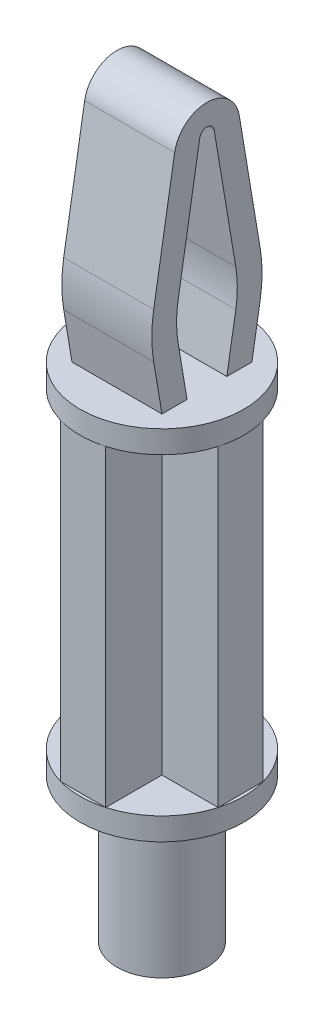
SolidWorks part; units mm, degrees
ref_plane "Front Plane" through (0, 0, 0) normal (0, 0, 1) x (1, 0, 0)
ref_plane "Top Plane" through (0, 0, 0) normal (0, 1, 0) x (1, 0, 0)
ref_plane "Right Plane" through (0, 0, 0) normal (1, 0, 0) x (0, 0, -1)
sketch "Sketch1" plane through (0, 0, 0) normal (0, 1, 0) x (1, 0, 0)
  line L0 (-5, 0) -> (5, 0) construction
  line L1 (-1, -3.5) -> (1, -3.5)
  line L2 (-1, -3.5) -> (-1, -1)
  line L3 (-1, 3.5) -> (1, 3.5)
  line L4 (1, -3.5) -> (1, -1)
  line L5 (-1, -3.5) -> (1, 3.5) construction
  line L6 (-1, 3.5) -> (1, -3.5) construction
  line L7 (-3.5, 1) -> (-1, 1)
  line L8 (-3.5, 1) -> (-3.5, -1)
  line L9 (-3.5, -1) -> (-1, -1)
  line L10 (3.5, 1) -> (3.5, -1)
  line L11 (-3.5, 1) -> (3.5, -1) construction
  line L12 (-3.5, -1) -> (3.5, 1) construction
  line L13 (0, 5) -> (0, -5) construction
  line L14 (1, 1) -> (1, 3.5)
  line L15 (-1, 1) -> (-1, 3.5)
  line L17 (1, -1) -> (3.5, -1)
  line L18 (1, 1) -> (3.5, 1)
  point P0 (0, 0)
  point P6 (0, 0)
  dimension "D1" = 7
  dimension "D2" = 10
  dimension "D3" = 10
  dimension "D4" = 2
extrude "Boss-Extrude1" add sketch "Sketch1" along normal mid plane 13.9
sketch "Sketch2" plane through (0, 6.95, 0) normal (0, 1, 0) x (1, 0, 0)
  circle A0 centre (0, 0) radius 3.6401
extrude "Boss-Extrude2" add sketch "Sketch2" along normal blind 1
mirror "Mirror1" about plane through (0, 0, 0) normal (0, 1, 0) of "Boss-Extrude2"
sketch "Sketch3" plane through (0, -7.95, 0) normal (0, 1, 0) x (1, 0, 0)
  circle A0 centre (0, 0) radius 2
  dimension "D1" = 4
extrude "Boss-Extrude4" add sketch "Sketch3" against normal blind 6.4
sketch "Sketch6" plane through (0, 0, 0) normal (1, 0, 0) x (0, 0, -1)
  line L0 (0, 7.95) -> (0, 19.8134) construction
  line L1 (3.6401, 7.95) -> (-3.6401, 7.95) construction
  line L2 (-2, 7.95) -> (-2.3666, 10.145)
  line L3 (-2.3666, 12.155) -> (-1.4357, 17.7282)
  line L4 (-1.4357, 17.7282) -> (0, 17.7282) construction
  line L5 (0, 17.7282) -> (1.4357, 17.7282) construction
  line L6 (2, 7.95) -> (2.3666, 10.145)
  line L7 (2.3666, 12.155) -> (1.4357, 17.7282)
  line L8 (0.8848, 7.95) -> (1.2817, 10.3262)
  line L9 (1.2817, 11.9738) -> (0.3205, 17.7282)
  line L10 (-0.8848, 7.95) -> (-1.2817, 10.3262)
  line L11 (-1.2817, 11.9738) -> (-0.3205, 17.7282)
  line L12 (-4.9745, 11.15) -> (4.6238, 11.15) construction
  line L13 (1.4357, 17.7282) -> (0.3507, 17.547) construction
  line L14 (-1.4357, 17.7282) -> (-0.3507, 17.547) construction
  line L15 (2, 7.95) -> (0.915, 8.1312) construction
  line L16 (-2, 7.95) -> (-0.915, 8.1312) construction
  line L17 (-2, 7.95) -> (-0.8848, 7.95)
  line L18 (0.8848, 7.95) -> (2, 7.95)
  arc A0 (-1.4357, 17.7282) -> (1.4357, 17.7282) centre (0, 17.4884) cw
  arc A1 (-0.3205, 17.7282) -> (0.3205, 17.7282) centre (0, 17.6747) cw
  arc A2 (1.2817, 11.9738) -> (1.2817, 10.3262) centre (-3.65, 11.15) cw
  arc A3 (-1.2817, 11.9738) -> (-1.2817, 10.3262) centre (3.65, 11.15) ccw
  arc A4 (2.3666, 12.155) -> (2.3666, 10.145) centre (-3.65, 11.15) cw
  arc A5 (-2.3666, 12.155) -> (-2.3666, 10.145) centre (3.65, 11.15) ccw
  point P22 (1.4193, 11.15)
  point P25 (-1.4193, 11.15)
  point P28 (2.5345, 11.15)
  point P31 (-2.5345, 11.15)
  point P32 (0, 18.944)
  dimension "D1" = 5
  dimension "D5" = 7.3
  dimension "D2" = 10.994
  dimension "D3" = 1.1
  dimension "D4" = 4
  dimension "D6" = 3.2
extrude "Boss-Extrude5" add sketch "Sketch6" along normal mid plane 4
